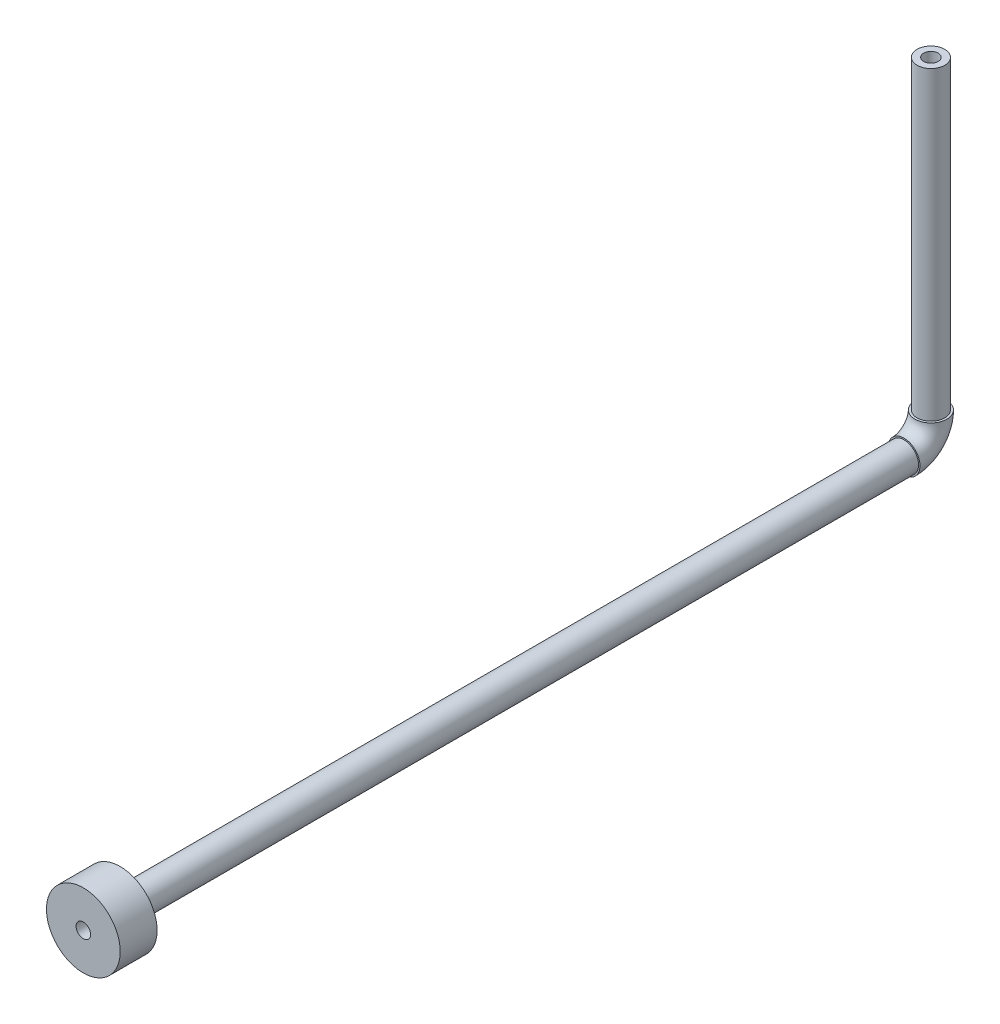
SolidWorks part; units mm, degrees
ref_plane "Front" through (0, 0, 0) normal (0, 0, 1) x (1, 0, 0)
ref_plane "Top" through (0, 0, 0) normal (0, 1, 0) x (1, 0, 0)
ref_plane "Right" through (0, 0, 0) normal (1, 0, 0) x (0, 0, -1)
other "Configuration Table"
sketch "Sketch1" plane through (0, 0, 0) normal (0, 0, 1) x (1, 0, 0)
  circle A0 centre (563.6927, 231.718) radius 5 construction
  circle A1 centre (563.6927, 231.718) radius 5
  circle A2 centre (563.6927, 231.718) radius 12.7
  dimension "D1" = 25.4
extrude "Base-Extrude" add sketch "Sketch1" against normal blind 12.7
sketch "Sketch2" plane through (0, 0, 0) normal (0, 0, 1) x (1, 0, 0)
  circle A0 centre (563.6927, 231.718) radius 5 construction
  circle A1 centre (563.6927, 231.718) radius 5
  circle A2 centre (563.6927, 231.718) radius 2.5 construction
  circle A3 centre (563.6927, 231.718) radius 2.5
  point P5 (563.6927, 248.7786)
extrude "Boss-Extrude1" add sketch "Sketch2" against normal blind 282.575
sketch "Sketch5" plane through (0, 0, -282.575) normal (0, 0, -1) x (-1, 0, 0)
  circle A0 centre (-563.6927, 231.718) radius 2.5 construction
  circle A1 centre (-563.6927, 231.718) radius 2.5
  circle A3 centre (-563.6927, 231.718) radius 5.5
  dimension "D1" = 11
ref_plane "Plane2" through (563.6927, 0, 0) normal (1, 0, 0) x (0, 0, -1)
sketch "Sketch6" plane through (563.6927, 0, 0) normal (1, 0, 0) x (0, 0, -1)
  line L0 (282.575, 226.718) -> (282.575, 236.718) construction
  line L1 (282.575, 226.718) -> (282.575, 236.718) construction
  line L2 (282.575, 236.718) -> (282.575, 240.9871) construction
  line L3 (282.575, 240.9871) -> (291.8441, 240.9871) construction
  arc A0 (282.575, 231.718) -> (291.8441, 240.9871) centre (282.575, 240.9871) ccw
sweep "Boss-Sweep2" add profiles "Sketch5" path "Sketch6"
sketch "Sketch7" plane through (0, 240.9871, 0) normal (0, 1, 0) x (-1, 0, 0)
  circle A0 centre (-563.6927, -291.8441) radius 2.5 construction
  circle A1 centre (-563.6927, -291.8441) radius 2.5
  circle A2 centre (-563.6927, -291.8441) radius 4.7625
  dimension "D1" = 9.525
extrude "Boss-Extrude2" add sketch "Sketch7" along normal blind 105.156
